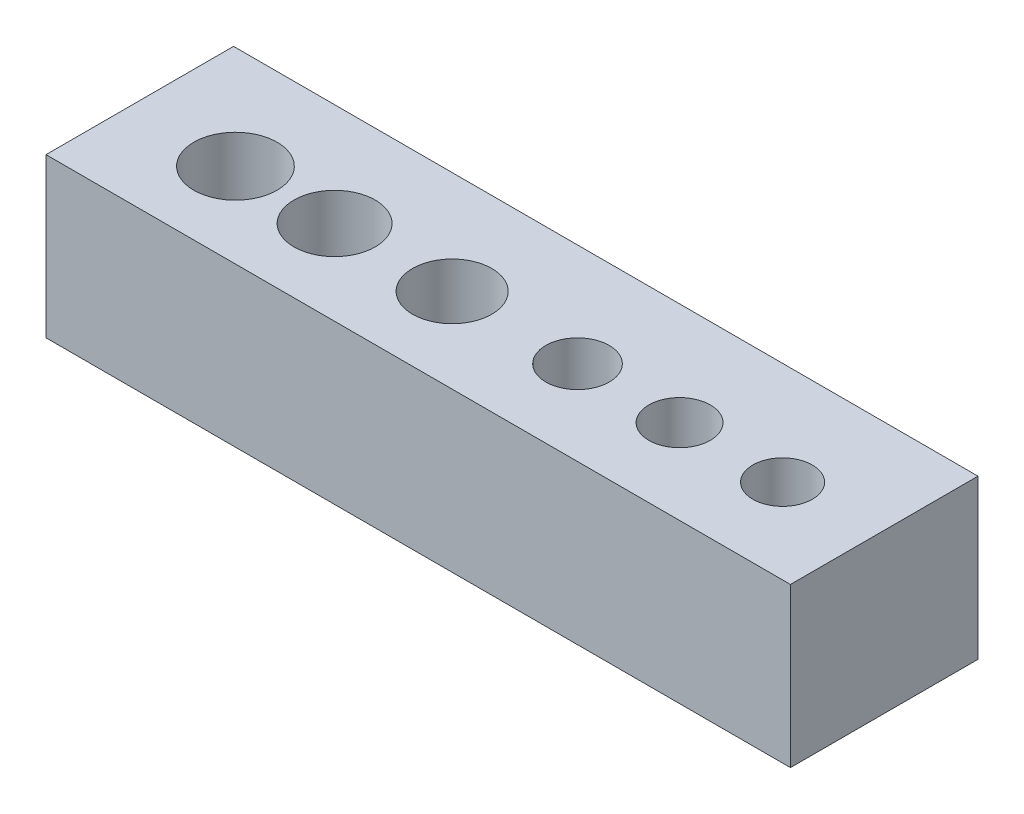
SolidWorks part; units mm, degrees
ref_plane "Front Plane" through (0, 0, 0) normal (0, 0, 1) x (1, 0, 0)
ref_plane "Top Plane" through (0, 0, 0) normal (0, 1, 0) x (1, 0, 0)
ref_plane "Right Plane" through (0, 0, 0) normal (1, 0, 0) x (0, 0, -1)
sketch "Sketch1" plane through (0, 0, 0) normal (0, 1, 0) x (1, 0, 0)
  line L9 (-18.769, -4.1899) -> (18.769, -4.1899)
  line L10 (-18.769, -4.1899) -> (-18.769, 5.268)
  line L11 (-18.769, 5.268) -> (18.769, 5.268)
  line L12 (18.769, -4.1899) -> (18.769, 5.268)
  circle A5 centre (14.1026, 0.0807) radius 1.5
  circle A6 centre (8.9081, 0.0807) radius 1.55
  circle A7 centre (3.7626, 0.0807) radius 1.6
  circle A8 centre (-2.5591, 0.0807) radius 2
  circle A9 centre (-8.4872, 0.0807) radius 2.05
  circle A10 centre (-13.4872, 0.0807) radius 2.1
  point P0 (0, 0)
  dimension "D1" = 3
  dimension "D2" = 3.1
  dimension "D3" = 3.2
  dimension "D4" = 4
  dimension "D5" = 4.1
  dimension "D6" = 4.2
  dimension "D7" = 5
extrude "Boss-Extrude1" add sketch "Sketch1" along normal blind 8
